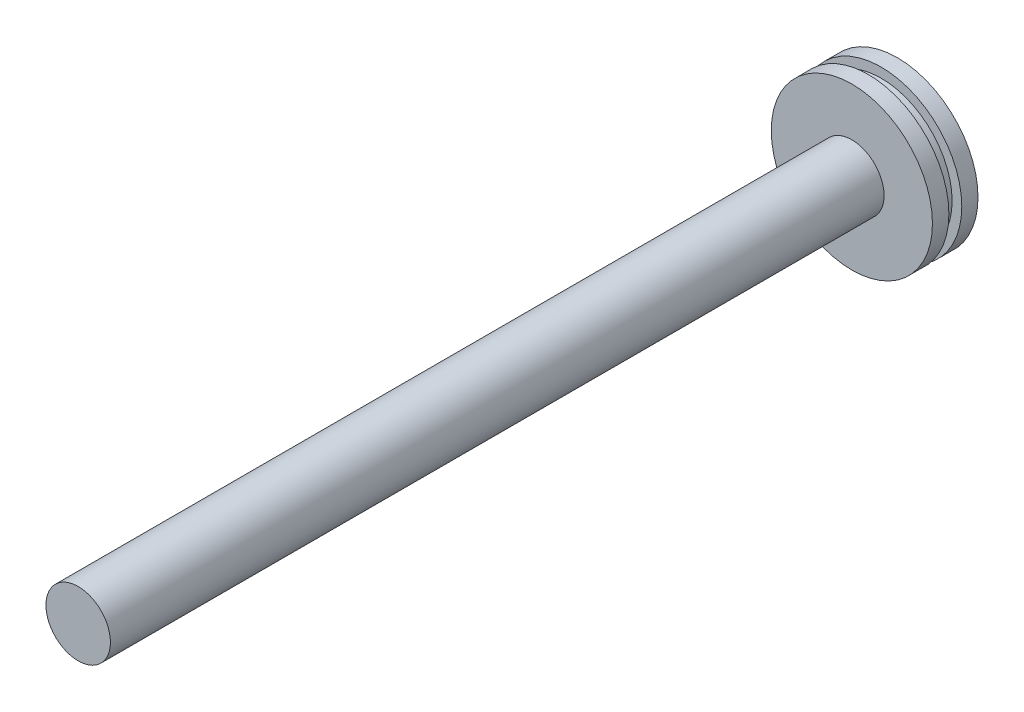
SolidWorks part; units mm, degrees
ref_plane "Front Plane" through (0, 0, 0) normal (0, 0, 1) x (1, 0, 0)
ref_plane "Top Plane" through (0, 0, 0) normal (0, 1, 0) x (1, 0, 0)
ref_plane "Right Plane" through (0, 0, 0) normal (1, 0, 0) x (0, 0, -1)
sketch "Sketch1" plane through (0, 0, 0) normal (0, 0, 1) x (1, 0, 0)
  circle A0 centre (0, 0) radius 50
extrude "Boss-Extrude1" add sketch "Sketch1" along normal blind 1200
sketch "Sketch2" plane through (0, 0, 0) normal (0, 0, -1) x (-1, 0, 0)
  circle A0 centre (0, 0) radius 125
extrude "Boss-Extrude2" add sketch "Sketch2" along normal blind 70.65
sketch "Sketch3" plane through (0, 0, -70.65) normal (0, 0, -1) x (-1, 0, 0)
  line L0 (-157.4614, 0) -> (158.8689, 0) construction
ref_plane "Plane1" through (125, 0, 0) normal (1, 0, 0) x (0, 0, -1)
sketch "Sketch4" plane through (0, 0, 1200) normal (0, 0, 1) x (1, 0, 0)
  line L0 (-158.8689, 0) -> (157.4614, 0) construction
ref_plane "Plane2" through (0, 0, 0) normal (0, 1, 0) x (1, 0, 0)
sketch "Sketch5" plane through (0, 0, 0) normal (0, 1, 0) x (1, 0, 0)
  line L0 (-125, 25.4866) -> (-125, 45.4866)
  line L2 (-125, 70.65) -> (-125, 0) construction
  line L3 (-125, 45.4866) -> (-110, 45.4866)
  line L4 (-110, 45.4866) -> (-110, 25.4866)
  line L5 (-110, 25.4866) -> (-125, 25.4866)
  point P5 (-125, 50.0733)
  point P6 (-125, 35.4866)
  dimension "D1" = 15
ref_axis "Axis1" through (0, 0, 1200) along (0, 0, -1)
revolve "Cut-Revolve1" cut sketch "Sketch5" angle 360 about axis through (0, 0, 1200) along (0, 0, -1)
